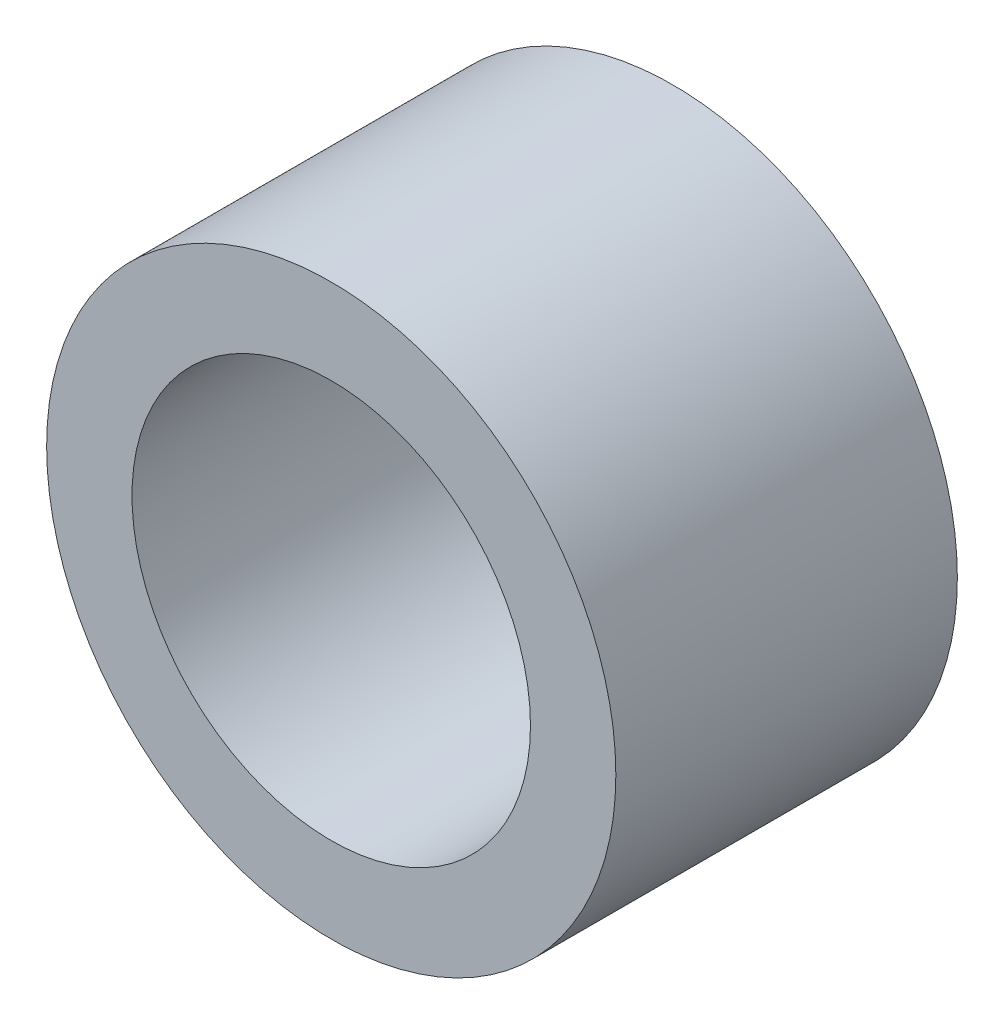
SolidWorks part; units mm, degrees
ref_plane "Front Plane" through (0, 0, 0) normal (0, 0, 1) x (1, 0, 0)
ref_plane "Top Plane" through (0, 0, 0) normal (0, 1, 0) x (1, 0, 0)
ref_plane "Right Plane" through (0, 0, 0) normal (1, 0, 0) x (0, 0, -1)
sketch "Sketch1" plane through (0, 0, 0) normal (0, 0, 1) x (1, 0, 0)
  circle A0 centre (-5.9081, 2.155) radius 2.5
  circle A1 centre (-5.9081, 2.155) radius 1.75
  dimension "D1" = 5
  dimension "D2" = 3.5
extrude "Boss-Extrude1" add sketch "Sketch1" along normal blind 3
